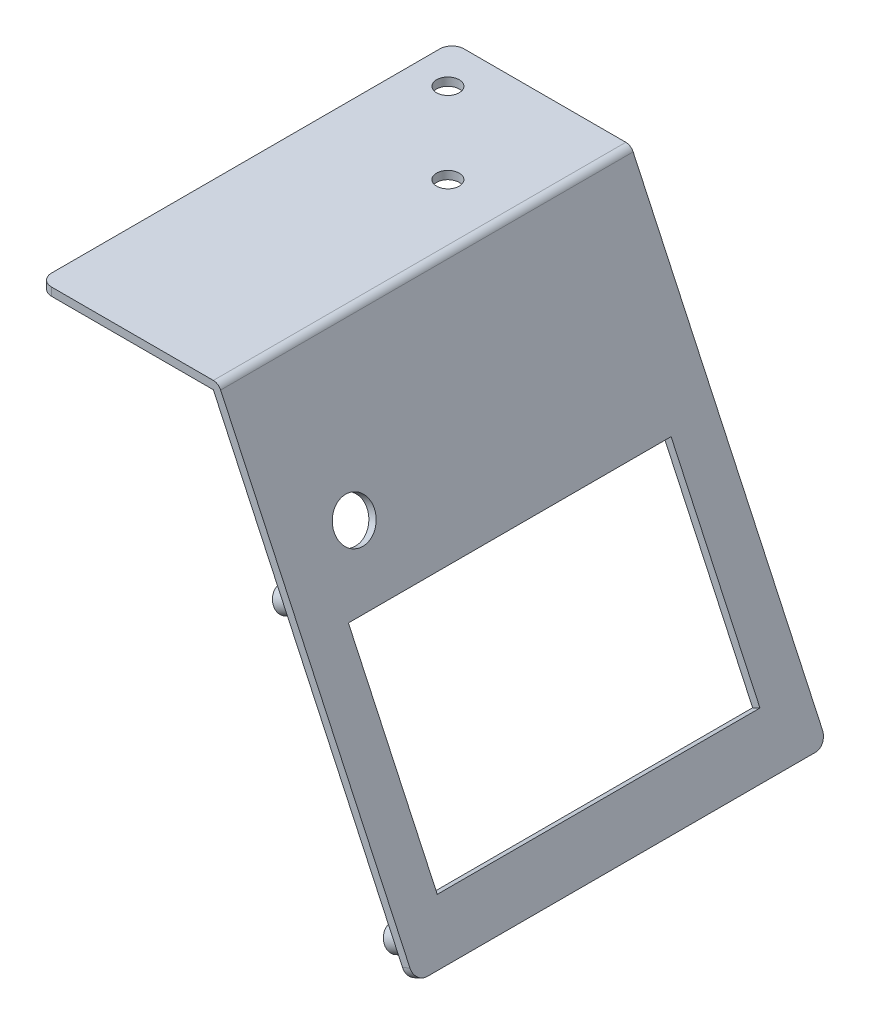
SolidWorks part; units mm, degrees
ref_plane "Front Plane" through (0, 0, 0) normal (0, 0, 1) x (1, 0, 0)
ref_plane "Top Plane" through (0, 0, 0) normal (0, 1, 0) x (1, 0, 0)
ref_plane "Right Plane" through (0, 0, 0) normal (1, 0, 0) x (0, 0, -1)
ref_plane "Plane1" through (0, 0, 0) normal (0, 0, -1) x (-1, 0, 0)
sketch "Sketch1" plane through (0, 0, 0) normal (0, 0, -1) x (-1, 0, 0)
  line L0 (-91.0626, -105.0706) -> (-43, -2)
  line L1 (-43, -2) -> (0, -2)
  line L2 (0, -2) -> (0, 0)
  line L3 (0, 0) -> (-44.2741, 0)
  line L4 (-44.2741, 0) -> (-92.8752, -104.2254)
  line L5 (-92.8752, -104.2254) -> (-91.0626, -105.0706)
extrude "Boss-Extrude1" add sketch "Sketch1" against normal blind 102
sketch "Sketch2" plane through (36.3665, 16.958, 0) normal (0.9063, 0.4226, 0) x (0, 0, -1)
  line L0 (-11.5, -69.4056) -> (-91.3, -69.4056)
  line L1 (-91.3, -69.4056) -> (-91.3, -121.4056)
  line L2 (-91.3, -121.4056) -> (-11.5, -121.4056)
  line L3 (-11.5, -121.4056) -> (-11.5, -69.4056)
extrude "Cut-Extrude1" cut sketch "Sketch2" against normal through all
ref_plane "Plane2" through (0, 0, 95.95) normal (0, 0, -1) x (-1, 0, 0)
sketch "Sketch3" plane through (0, 0, 95.95) normal (0, 0, -1) x (-1, 0, 0)
  line L0 (-56.0838, -46.6217) -> (-54.8159, -43.9027)
  line L1 (-54.8159, -43.9027) -> (-61.1601, -40.9444)
  line L2 (-61.1601, -40.9444) -> (-62.4279, -43.6633)
  line L3 (-62.4279, -43.6633) -> (-56.0838, -46.6217)
  line L4 (-53.7745, -44.3883) -> (-62.2015, -40.4588) construction
revolve "Revolve1" add sketch "Sketch3" angle 360 about L4
sketch "Sketch4" plane through (0, 0, 95.95) normal (0, 0, -1) x (-1, 0, 0)
  line L0 (-83.5117, -105.441) -> (-82.2438, -102.7221)
  line L1 (-82.2438, -102.7221) -> (-88.588, -99.7638)
  line L2 (-88.588, -99.7638) -> (-89.8559, -102.4827)
  line L3 (-89.8559, -102.4827) -> (-83.5117, -105.441)
  line L4 (-81.2024, -103.2077) -> (-89.6294, -99.2782) construction
revolve "Revolve2" add sketch "Sketch4" angle 360 about L4
ref_plane "Plane3" through (0, 0, 8.05) normal (0, 0, -1) x (-1, 0, 0)
sketch "Sketch5" plane through (0, 0, 8.05) normal (0, 0, -1) x (-1, 0, 0)
  line L0 (-83.5117, -105.441) -> (-82.2438, -102.7221)
  line L1 (-82.2438, -102.7221) -> (-88.588, -99.7638)
  line L2 (-88.588, -99.7638) -> (-89.8559, -102.4827)
  line L3 (-89.8559, -102.4827) -> (-83.5117, -105.441)
  line L4 (-81.2024, -103.2077) -> (-89.6294, -99.2782) construction
revolve "Revolve3" add sketch "Sketch5" angle 360 about L4
sketch "Sketch6" plane through (0, 0, 8.05) normal (0, 0, -1) x (-1, 0, 0)
  line L0 (-56.0838, -46.6217) -> (-54.8159, -43.9027)
  line L1 (-54.8159, -43.9027) -> (-61.1601, -40.9444)
  line L2 (-61.1601, -40.9444) -> (-62.4279, -43.6633)
  line L3 (-62.4279, -43.6633) -> (-56.0838, -46.6217)
  line L4 (-53.7745, -44.3883) -> (-62.2015, -40.4588) construction
revolve "Revolve4" add sketch "Sketch6" angle 360 about L4
hole_wizard "Ø10.0 (10) Diameter Hole1" positions "Sketch8" profile "Sketch7" hole size "Ø10.0" standard "ANSI Metric"
sketch "Sketch8" plane through (34.5539, 16.1127, 0) normal (-0.9063, -0.4226, 0) x (0, 0, 1)
  point P0 (83.1, -53.4056)
sketch "Sketch7" plane through (57.1241, -32.2892, 83.1) normal (0, 0, 1) x (0.4226, -0.9063, 0)
  line L0 (0, 0) -> (0, 46.0476)
  line L1 (0, 46.0476) -> (5, 46.0476)
  line L2 (5, 46.0476) -> (5, 0)
  line L5 (5, 0) -> (0, 0)
  line L11 (0, -6.35) -> (0, 107.95) construction
  dimension "Thru Hole Dia." = 10
  dimension "Thru Hole Depth" = 46.0476
hole_wizard "Ø5.6 (5.6) Diameter Hole1" positions "Sketch10" profile "Sketch9" hole size "Ø5.6" standard "ANSI Metric"
sketch "Sketch10" plane through (0, -2, 0) normal (0, -1, 0) x (-1, 0, 0)
  line L0 (-43, 0) -> (0, 0) construction
  point P0 (-29, -30)
  point P1 (-9, -10)
  dimension "D1" = 20
  dimension "D2" = 20
  dimension "D3" = 10
sketch "Sketch9" plane through (29, -2, 30) normal (1, 0, 0) x (0, 0, -1)
  line L0 (0, 0) -> (0, 2)
  line L1 (0, 2) -> (2.8, 2)
  line L2 (2.8, 2) -> (2.8, 0)
  line L5 (2.8, 0) -> (0, 0)
  line L11 (0, -6.35) -> (0, 107.95) construction
  dimension "Thru Hole Dia." = 5.6
  dimension "Thru Hole Depth" = 2
hole_wizard "Ø2.7 (2.7) Diameter Hole1" positions "Sketch12" profile "Sketch11" hole size "Ø2.7" standard "ANSI Metric"
sketch "Sketch12" plane through (28.2097, 13.1544, 0) normal (-0.9063, -0.4226, 0) x (0, 0, 1)
  point P0 (8.05, -62.9556)
  point P1 (8.05, -127.8556)
  point P2 (95.95, -127.8556)
  point P3 (95.95, -62.9556)
sketch "Sketch11" plane through (54.8159, -43.9027, 8.05) normal (0, 0, 1) x (0.4226, -0.9063, 0)
  line L0 (0, 0) -> (0, 7)
  line L1 (0, 7) -> (1.35, 7)
  line L2 (1.35, 7) -> (1.35, 0)
  line L5 (1.35, 0) -> (0, 0)
  line L10 (0, 7) -> (-1.35, 7) construction
  line L11 (0, -6.35) -> (0, 107.95) construction
  dimension "Hole Dia." = 2.7
  dimension "Hole Depth" = 7
  dimension "Drill Angle" = 180
fillet "Fillet1" radius 2 1 edges at (44.2741, 0, 51)
fillet "Fillet2" radius 3 4 edges at (91.9689, -104.648, 102) (0, -1, 0) (0, -1, 102) (91.9689, -104.648, 0)
